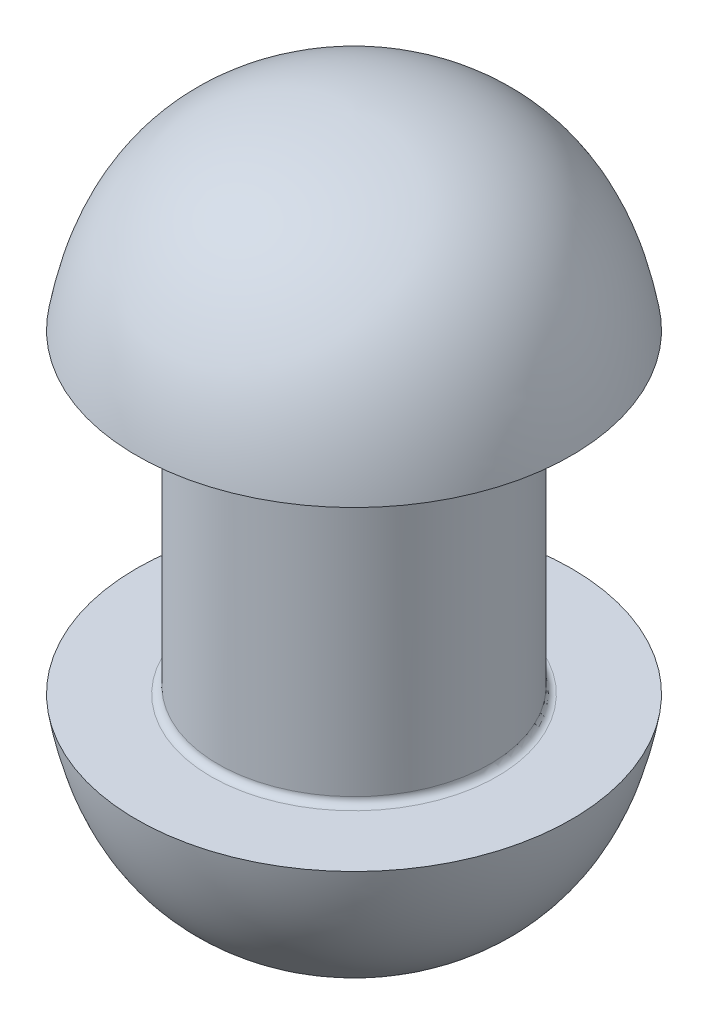
SolidWorks part; units mm, degrees
ref_plane "Front Plane" through (0, 0, 0) normal (0, 0, 1) x (1, 0, 0)
ref_plane "Top Plane" through (0, 0, 0) normal (0, 1, 0) x (1, 0, 0)
ref_plane "Right Plane" through (0, 0, 0) normal (1, 0, 0) x (0, 0, -1)
sketch "Sketch1" plane through (0, 0, 0) normal (0, 1, 0) x (1, 0, 0)
  circle A0 centre (0, 0) radius 9.4868
extrude "Boss-Extrude1" add sketch "Sketch1" along normal blind 11 contours A0
sketch "Sketch2" plane through (0, 0, 0) normal (0, 0, 1) x (1, 0, 0)
  line L0 (0, 0) -> (0, 27.196) construction
  line L1 (0, 11) -> (-22.4565, 11) construction
  line L2 (9.4868, 11) -> (-9.4868, 11) construction
  line L3 (0, 24.2816) -> (0, 11)
  line L4 (0, 11) -> (-15.1789, 11)
  spline S0 degree 2 poles (0, 24.2816) (-13.0156, 23.9673) (-15.1789, 11) knots 0 0 0 1 1 1
  dimension "parh" = 3.3204
  dimension "pard" = 5.0596
revolve "Revolve1" add sketch "Sketch2" angle 360 about L0
mirror "Mirror1" about plane through (0, 0, 0) normal (0, 1, 0) of "Boss-Extrude1", "Revolve1"
fillet "Fillet1" radius 0.5 2 edges at (0, -11, -9.4868) (0, 11, 9.4868)
equation "\"dr\"= 6 * sqr ( \"t\" )"
equation "\"dia@Sketch1\"=\"dr\""
equation "\"t\"= 10"
equation "\"headh@Sketch2\" = 0.7 * \"dr\""
equation "\"headr@Sketch2\"=0.8*\"dr\""
equation "\"parh@Sketch2\" = \"headh@Sketch2\" / 4"
equation "\"pard@Sketch2\"=\"headr@Sketch2\"/3"
